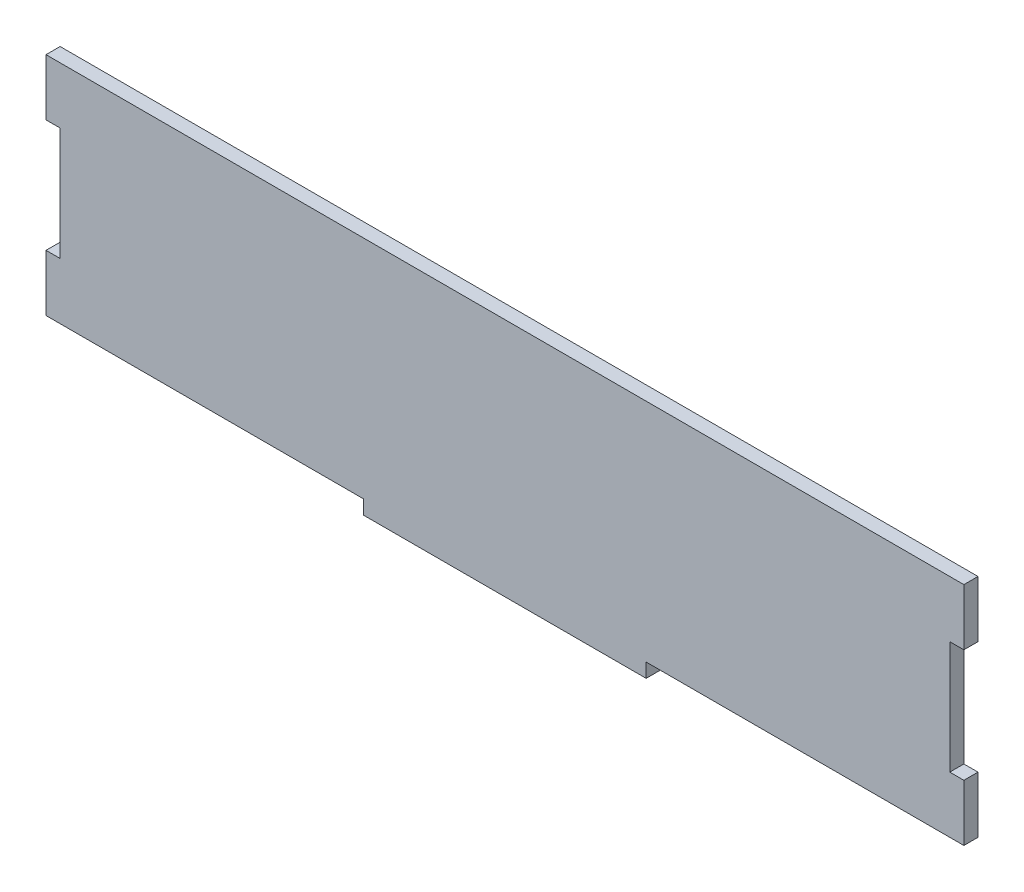
SolidWorks part; units mm, degrees
ref_plane "Ebene vorne" through (0, 0, 0) normal (0, 0, 1) x (1, 0, 0)
ref_plane "Ebene oben" through (0, 0, 0) normal (0, 1, 0) x (1, 0, 0)
ref_plane "Ebene rechts" through (0, 0, 0) normal (1, 0, 0) x (0, 0, -1)
sketch "Skizze1" plane through (0, 0, 0) normal (0, 0, 1) x (1, 0, 0)
  line L1 (0, 0) -> (325, 0)
  line L2 (0, 0) -> (0, 80)
  line L3 (0, 80) -> (325, 80)
  line L4 (325, 0) -> (325, 80)
  dimension "D1" = 325
  dimension "D2" = 80
extrude "Aufsatz-Linear austragen1" add sketch "Skizze1" along normal blind 5
sketch "Skizze2" plane through (0, 0, 5) normal (0, 0, 1) x (1, 0, 0)
  line L0 (162.5, 80) -> (162.5, 0) construction
  line L1 (325, 80) -> (0, 80) construction
  line L2 (0, 0) -> (325, 0) construction
  line L3 (212.5, 0) -> (112.5, 0)
  line L4 (112.5, 0) -> (112.5, -5)
  line L5 (112.5, -5) -> (212.5, -5)
  line L6 (212.5, 0) -> (212.5, -5)
  point P10 (162.5, -5)
  dimension "D1" = 5
  dimension "D2" = 100
extrude "Aufsatz-Linear austragen3" add sketch "Skizze2" against normal through all
sketch "Skizze3" plane through (0, 0, 5) normal (0, 0, 1) x (1, 0, 0)
  line L0 (162.5, 80) -> (162.5, 40) construction
  line L1 (325, 80) -> (0, 80) construction
  line L2 (162.5, 40) -> (0, 40) construction
  line L3 (0, 80) -> (0, 0) construction
  line L4 (0, 20) -> (0, 60)
  line L5 (0, 60) -> (5, 60)
  line L6 (5, 60) -> (5, 20)
  line L7 (0, 20) -> (5, 20)
  line L8 (325, 20) -> (320, 20)
  line L9 (320, 60) -> (320, 20)
  line L10 (325, 60) -> (320, 60)
  line L11 (325, 20) -> (325, 60)
  point P11 (5, 40)
  point P16 (320, 40)
  dimension "D1" = 40
  dimension "D2" = 5
extrude "Schnitt-Linear austragen1" cut sketch "Skizze3" against normal through all
